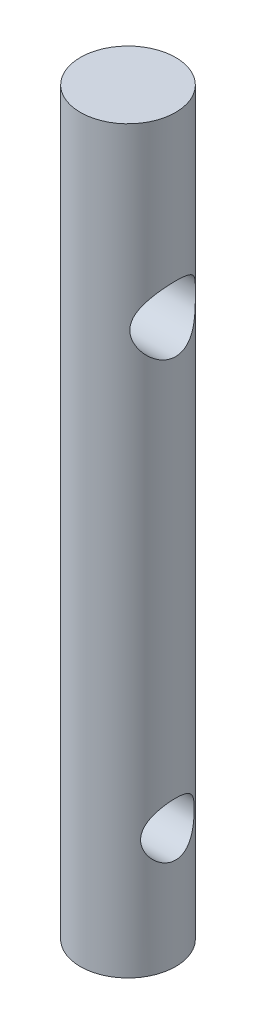
SolidWorks part; units mm, degrees
ref_plane "Front Plane" through (0, 0, 0) normal (0, 0, 1) x (1, 0, 0)
ref_plane "Top Plane" through (0, 0, 0) normal (0, 1, 0) x (1, 0, 0)
ref_plane "Right Plane" through (0, 0, 0) normal (1, 0, 0) x (0, 0, -1)
sketch "Sketch1" plane through (0, 0, 0) normal (0, 1, 0) x (1, 0, 0)
  circle A0 centre (0, 0) radius 4
  dimension "D1" = 8
extrude "Boss-Extrude1" add sketch "Sketch1" along normal blind 62.1
ref_plane "Plane1" through (-4, 0, 0) normal (-1, 0, 0) x (0, 0, 1)
sketch "Sketch2" plane through (-4, 0, 0) normal (1, 0, 0) x (0, 0, -1)
  line L0 (-4, 0) -> (4, 0) construction
  line L1 (4, 62.1) -> (-4, 62.1) construction
  circle A0 centre (0, 47.1) radius 2.5
  circle A1 centre (0, 10) radius 2
  point P0 (0, 47.1)
  dimension "D3" = 5
  dimension "D4" = 4
  dimension "D1" = 10
  dimension "D2" = 15
hole_wizard "M5 Clearance Hole1" positions "Sketch2" profile "Sketch3" hole size "M5" standard "ANSI Metric" end condition through all
sketch "Sketch3" plane through (-4, 47.1, 0) normal (0, 1, 0) x (0, 0, 1)
  line L0 (0, 0) -> (0, 8)
  line L1 (0, 8) -> (2.75, 8)
  line L2 (2.75, 8) -> (2.75, 0)
  line L5 (2.75, 0) -> (0, 0)
  line L11 (0, -6.35) -> (0, 107.95) construction
  dimension "Thru Hole Dia." = 5.5
  dimension "Thru Hole Depth" = 8
sketch "Sketch5" plane through (-4, 0, 0) normal (-1, 0, 0) x (0, 0, 1)
  point P0 (0, 10)
hole_wizard "M4 Clearance Hole1" positions "Sketch5" profile "Sketch6" hole size "M4" standard "ANSI Metric" end condition through all
sketch "Sketch6" plane through (-4, 10, 0) normal (0, 1, 0) x (0, 0, 1)
  line L0 (0, 0) -> (0, 8)
  line L1 (0, 8) -> (2.25, 8)
  line L2 (2.25, 8) -> (2.25, 0)
  line L5 (2.25, 0) -> (0, 0)
  line L11 (0, -6.35) -> (0, 107.95) construction
  dimension "Thru Hole Dia." = 4.5
  dimension "Thru Hole Depth" = 8
